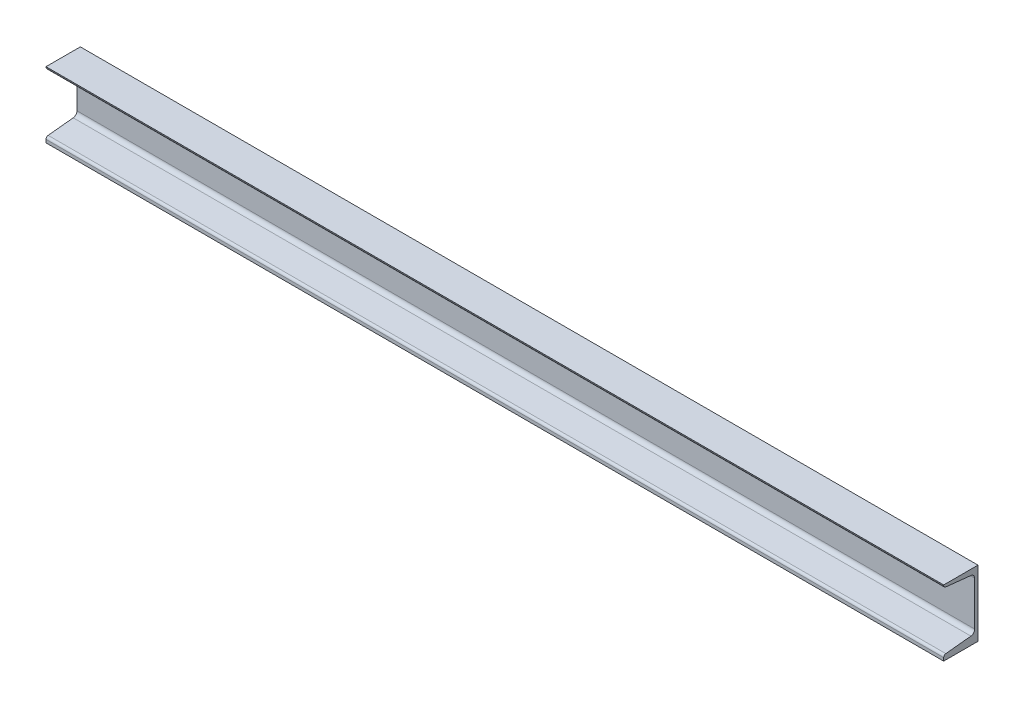
SolidWorks part; units mm, degrees
ref_plane "Front Plane" through (0, 0, 0) normal (0, 0, 1) x (1, 0, 0)
ref_plane "Top Plane" through (0, 0, 0) normal (0, 1, 0) x (1, 0, 0)
ref_plane "Right Plane" through (0, 0, 0) normal (1, 0, 0) x (0, 0, -1)
sketch "Sketch1" plane through (0, 0, 0) normal (0, 1, 0) x (1, 0, 0)
  line L0 (0, 0) -> (-1700, 0)
other "C channel 120 X 12(1)"
ref_plane "Plane1" through (0, 0, 0) normal (-1, 0, 0) x (0, 0, 1)
sketch "Sketch12" plane through (0, 0, 0) normal (-1, 0, 0) x (0, 0, 1)
  line L0 (65, 125) -> (0, 125)
  line L1 (65, 0) -> (0, 0)
  line L2 (0, 125) -> (0, 0)
  line L6 (65, 125) -> (65, 124.1647)
  line L7 (65, 0) -> (65, 5.8453)
  line L12 (6.3, 106.74) -> (6.3, 23.27)
  line L17 (13.4638, 114.6962) -> (60.9704, 119.6893)
  line L18 (13.4638, 15.3138) -> (60.9704, 10.3207)
  arc A0 (60.9704, 119.6893) -> (65, 124.1647) centre (60.5, 124.1647) ccw
  arc A1 (60.9704, 10.3207) -> (65, 5.8453) centre (60.5, 5.8453) cw
  arc A9 (6.3, 23.27) -> (13.4638, 15.3138) centre (14.3, 23.27) ccw
  arc A10 (6.3, 106.74) -> (13.4638, 114.6962) centre (14.3, 106.74) cw
  point P8 (0, 62.5)
  point P9 (6.3, 65.005)
  point P10 (32.5, 125)
  point P11 (32.5, 0)
  point P12 (65, 9.8971)
  point P13 (65, 120.1129)
  point P14 (0, 0)
  dimension "D4" = 4.5
  dimension "RI" = 8
  dimension "D2" = 6
  dimension "D3" = 18.26
  dimension "Depth" = 125
  dimension "BF" = 65
  dimension "TW" = 6.3
  dimension "d1" = 83.47
